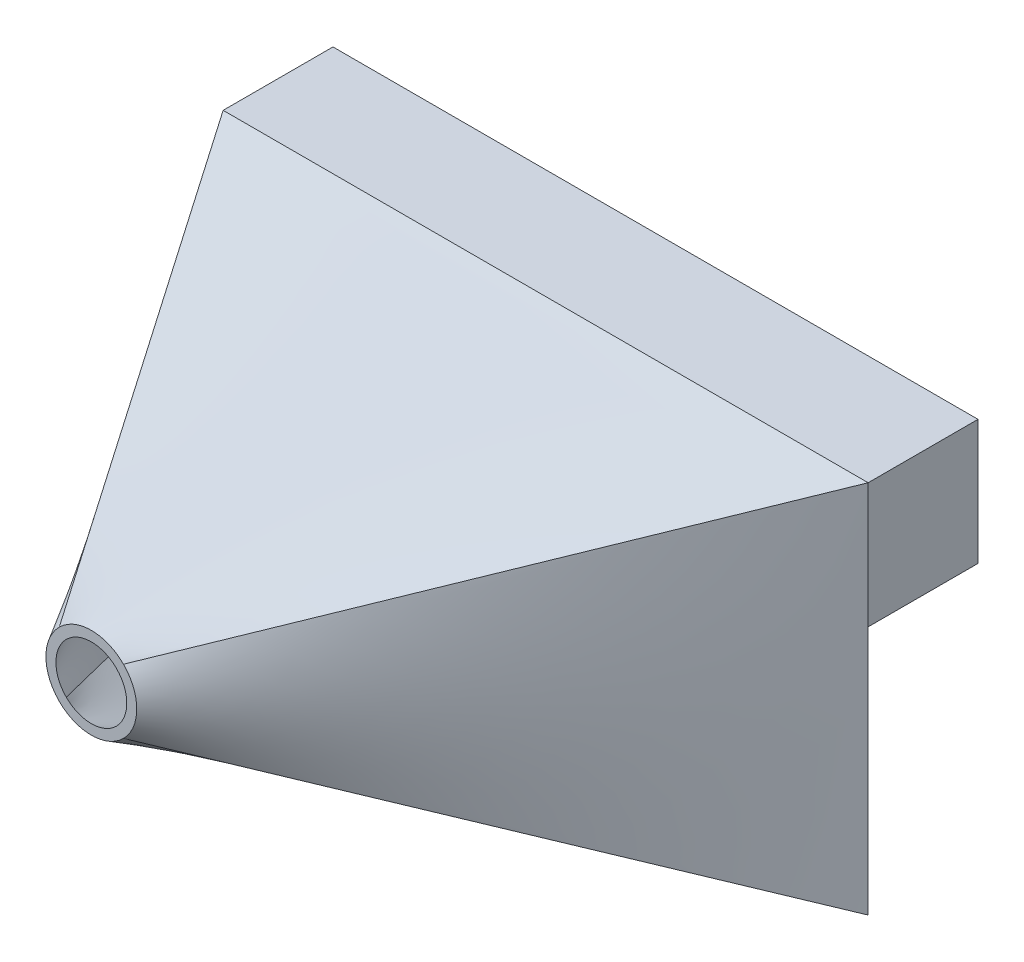
SolidWorks part; units mm, degrees
ref_plane "前视基准面" through (0, 0, 0) normal (0, 0, 1) x (1, 0, 0)
ref_plane "上视基准面" through (0, 0, 0) normal (0, 1, 0) x (1, 0, 0)
ref_plane "右视基准面" through (0, 0, 0) normal (1, 0, 0) x (0, 0, -1)
sketch "草图1" plane through (0, 0, 0) normal (0, 0, 1) x (1, 0, 0)
  line L1 (-62.6, 35.5) -> (62.6, 35.5)
  line L2 (-62.6, 35.5) -> (-62.6, -35.5)
  line L3 (-62.6, -35.5) -> (62.6, -35.5)
  line L4 (62.6, 35.5) -> (62.6, -35.5)
  line L5 (-62.6, 35.5) -> (62.6, -35.5) construction
  line L6 (-62.6, -35.5) -> (62.6, 35.5) construction
  line L7 (-64.6, 37.5) -> (64.6, 37.5)
  line L8 (-64.6, 37.5) -> (-64.6, -37.5)
  line L9 (-64.6, -37.5) -> (64.6, -37.5)
  line L10 (64.6, 37.5) -> (64.6, -37.5)
  line L11 (-64.6, 37.5) -> (64.6, -37.5) construction
  line L12 (-64.6, -37.5) -> (64.6, 37.5) construction
  point P0 (0, 0)
  point P6 (0, 0)
  dimension "D1" = 125.2
  dimension "D2" = 71
  dimension "D3" = 129.2
  dimension "D4" = 75
extrude "凸台-拉伸1" add sketch "草图1" along normal blind 22
ref_plane "基准面1" through (0, 0, 96) normal (0, 0, 1) x (1, 0, 0)
ref_plane "基准面2" through (0, 0, 22) normal (0, 0, 1) x (1, 0, 0)
sketch "草图2" plane through (0, 0, 22) normal (0, 0, 1) x (1, 0, 0)
  line L0 (-64.6, 37.5) -> (-62.6, 35.5)
  line L1 (-62.6, 35.5) -> (62.6, 35.5)
  line L2 (62.6, 35.5) -> (64.6, 37.5)
  line L3 (64.6, 37.5) -> (-64.6, 37.5)
sketch "草图3" plane through (0, 0, 22) normal (0, 0, 1) x (1, 0, 0)
  line L0 (-62.6, 35.5) -> (-64.6, 37.5)
  line L1 (-64.6, 37.5) -> (-64.6, -37.5)
  line L2 (-64.6, -37.5) -> (-62.6, -35.5)
  line L3 (-62.6, -35.5) -> (-62.6, 35.5)
sketch "草图4" plane through (0, 0, 22) normal (0, 0, 1) x (1, 0, 0)
  line L0 (-62.6, -35.5) -> (-64.6, -37.5)
  line L1 (-64.6, -37.5) -> (64.6, -37.5)
  line L2 (64.6, -37.5) -> (62.6, -35.5)
  line L3 (62.6, -35.5) -> (-62.6, -35.5)
sketch "草图5" plane through (0, 0, 22) normal (0, 0, 1) x (1, 0, 0)
  line L0 (64.6, 37.5) -> (62.6, 35.5)
  line L1 (62.6, 35.5) -> (62.6, -35.5)
  line L2 (62.6, -35.5) -> (64.6, -37.5)
  line L3 (64.6, -37.5) -> (64.6, 37.5)
ref_plane "基准面3" through (0, -35.5, 0) normal (0, 1, 0) x (1, 0, 0)
sketch "草图6" plane through (0, 0, 96) normal (0, 0, 1) x (1, 0, 0)
  line L0 (0, 0) -> (50000, 0) construction
  line L1 (0, 0) -> (0, -50000) construction
  line L2 (-17, -1) -> (35338.3391, -35356.3391) construction
  line L3 (-17, -1) -> (-35372.3391, -35356.3391) construction
  line L4 (-22.0205, 4.0205) -> (-23.4347, 5.4347)
  line L5 (-11.9795, 4.0205) -> (-10.5653, 5.4347)
  arc A0 (-11.9795, 4.0205) -> (-22.0205, 4.0205) centre (-17, -1) ccw
  arc A1 (-10.5653, 5.4347) -> (-23.4347, 5.4347) centre (-17, -1) ccw
  point P5 (-17, -1)
  point P10 (-22.0205, 4.0205)
  point P11 (-23.4347, 5.4347)
  point P12 (-10.5653, 5.4347)
  point P13 (-11.9795, 4.0205)
  dimension "D1" = 17
  dimension "D2" = 1
  dimension "D3" = 7.1
  dimension "D4" = 9.1
sketch "草图7" plane through (0, 0, 96) normal (0, 0, 1) x (1, 0, 0)
  line L0 (141404.3562, 141420.3562) -> (-176793.6953, -176777.6953) construction
  line L1 (-22.0205, 4.0205) -> (-23.4347, 5.4347) construction
  line L2 (-22.0205, 4.0205) -> (-23.4347, 5.4347)
  line L3 (-23.4347, -7.4347) -> (-22.0205, -6.0205)
  arc A0 (-22.0205, 4.0205) -> (-22.0205, -6.0205) centre (-17, -1) ccw
  arc A1 (-23.4347, -7.4347) -> (-23.4347, 5.4347) centre (-17, -1) cw
  point P0 (-22.0205, -6.0205)
  point P1 (-23.4347, -7.4347)
sketch "草图8" plane through (0, 0, 96) normal (0, 0, 1) x (1, 0, 0)
  line L0 (-141438.3562, 141420.3562) -> (176759.6953, -176777.6953) construction
  line L1 (-22.0205, -6.0205) -> (-23.4347, -7.4347)
  line L2 (-11.9795, -6.0205) -> (-10.5653, -7.4347)
  arc A0 (-22.0205, -6.0205) -> (-11.9795, -6.0205) centre (-17, -1) ccw
  arc A1 (-23.4347, -7.4347) -> (-10.5653, -7.4347) centre (-17, -1) ccw
  point P0 (-11.9795, -6.0205)
  point P1 (-10.5653, -7.4347)
sketch "草图9" plane through (0, 0, 96) normal (0, 0, 1) x (1, 0, 0)
  line L0 (-11.9795, 4.0205) -> (-10.5653, 5.4347) construction
  line L1 (-10.5653, 5.4347) -> (-11.9795, 4.0205)
  line L2 (-11.9795, -6.0205) -> (-10.5653, -7.4347)
  arc A0 (-11.9795, -6.0205) -> (-11.9795, 4.0205) centre (-17, -1) ccw
  arc A1 (-11.9795, 4.0205) -> (-22.0205, 4.0205) centre (-17, -1) ccw construction
  arc A2 (-10.5653, -7.4347) -> (-10.5653, 5.4347) centre (-17, -1) ccw
loft "放样1" add profiles "草图2", "草图6"
loft "放样2" add profiles "草图3", "草图7"
loft "放样3" add profiles "草图4", "草图8"
loft "放样4" add profiles "草图5", "草图9"
sketch "草图11" plane through (0, -35.5, 0) normal (0, 1, 0) x (1, 0, 0)
  line L0 (-62.6, 0) -> (62.6, 0)
  line L1 (62.6, -22) -> (62.6, 0) construction
  line L2 (62.6, 0) -> (62.6, -22)
  line L3 (62.6, -22) -> (-62.6, -22)
  line L4 (-62.6, -22) -> (-62.6, 0)
extrude "切除-拉伸1" cut sketch "草图11" against normal blind 10
ref_plane "基准面4" through (62.6, 0, 0) normal (-1, 0, 0) x (0, 0, 1)
sketch "草图12" plane through (62.6, 0, 0) normal (-1, 0, 0) x (0, 0, 1)
  line L0 (0, 37.5) -> (0, -37.5) construction
  line L1 (22, 37.5) -> (22, -37.5) construction
  line L2 (0, 12.5) -> (22, 12.5)
  line L3 (22, 12.5) -> (22, -37.5)
  line L4 (22, -37.5) -> (0, -37.5)
  line L5 (0, -37.5) -> (0, 12.5)
  point P0 (0, 12.5)
  point P1 (22, 12.5)
  dimension "D1" = 50
  dimension "D2" = 50
extrude "切除-拉伸2" cut sketch "草图12" against normal blind 10
